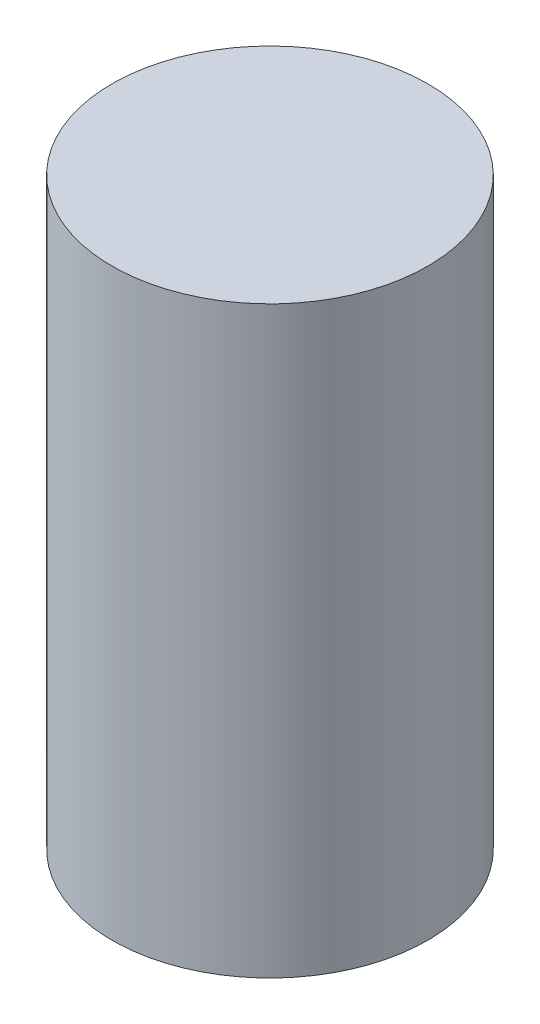
SolidWorks part; units mm, degrees
ref_plane "Front Plane" through (0, 0, 0) normal (0, 0, 1) x (1, 0, 0)
ref_plane "Top Plane" through (0, 0, 0) normal (0, 1, 0) x (1, 0, 0)
ref_plane "Right Plane" through (0, 0, 0) normal (1, 0, 0) x (0, 0, -1)
sketch "Sketch1" plane through (0, 0, 0) normal (0, 1, 0) x (1, 0, 0)
  circle A0 centre (0, 0) radius 33
  dimension "D1" = 66
extrude "Boss-Extrude1" add sketch "Sketch1" along normal blind 122
